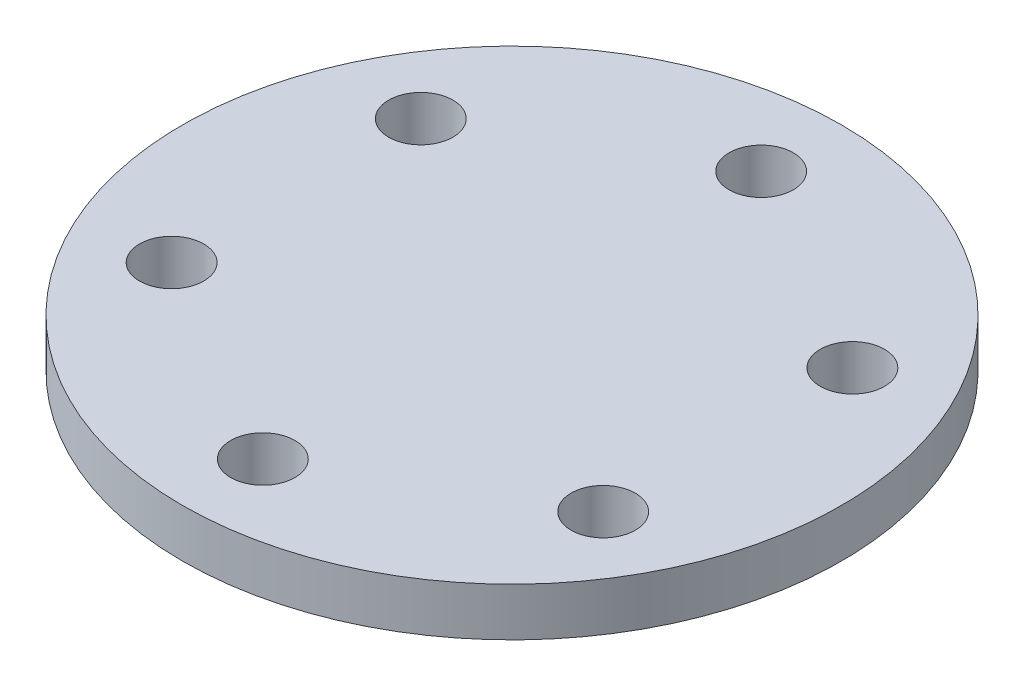
SolidWorks part; units mm, degrees
ref_plane "前基準面" through (0, 0, 0) normal (0, 0, 1) x (1, 0, 0)
ref_plane "上基準面" through (0, 0, 0) normal (0, 1, 0) x (1, 0, 0)
ref_plane "右基準面" through (0, 0, 0) normal (1, 0, 0) x (0, 0, -1)
sketch "草圖1" plane through (0, 0, 0) normal (0, 1, 0) x (1, 0, 0)
  circle A0 centre (0, 0) radius 20.5
  dimension "D1" = 41
extrude "填料-伸長1" add sketch "草圖1" along normal blind 3
sketch "草圖2" plane through (0, 3, 0) normal (0, 1, 0) x (1, 0, 0)
  circle A0 centre (0, 15.5) radius 2
  dimension "D1" = 4
  dimension "D2" = 15.5
extrude "除料-伸長1" cut sketch "草圖2" against normal up to next
pattern_circular "環狀複製排列1" count 6 over 360 about axis through (0, 0, 0) along (0, 1, 0) of "除料-伸長1"
